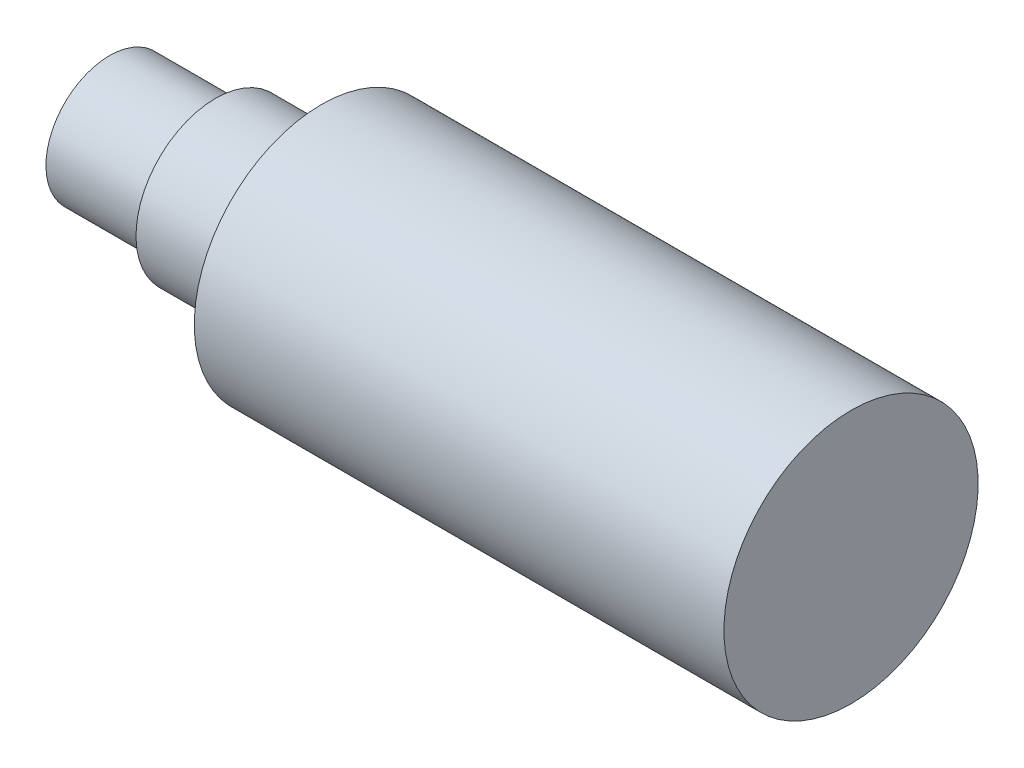
SolidWorks part; units mm, degrees
ref_plane "Front Plane" through (0, 0, 0) normal (0, 0, 1) x (1, 0, 0)
ref_plane "Top Plane" through (0, 0, 0) normal (0, 1, 0) x (1, 0, 0)
ref_plane "Right Plane" through (0, 0, 0) normal (1, 0, 0) x (0, 0, -1)
sketch "Sketch1" plane through (0, 0, 0) normal (0, 0, 1) x (1, 0, 0)
  line L0 (0, 0) -> (0, 6)
  line L1 (0, 6) -> (10, 6)
  line L2 (10, 6) -> (10, 7.5)
  line L3 (10, 7.5) -> (20, 7.5)
  line L4 (20, 7.5) -> (20, 12)
  line L5 (20, 12) -> (70, 12)
  line L6 (70, 12) -> (70, 0)
  line L7 (70, 0) -> (0, 0)
  dimension "D1" = 6
  dimension "D2" = 7.5
  dimension "D3" = 10
  dimension "D4" = 10
  dimension "D5" = 50
  dimension "D6" = 12
revolve "Revolve1" add sketch "Sketch1" angle 360 about L7
